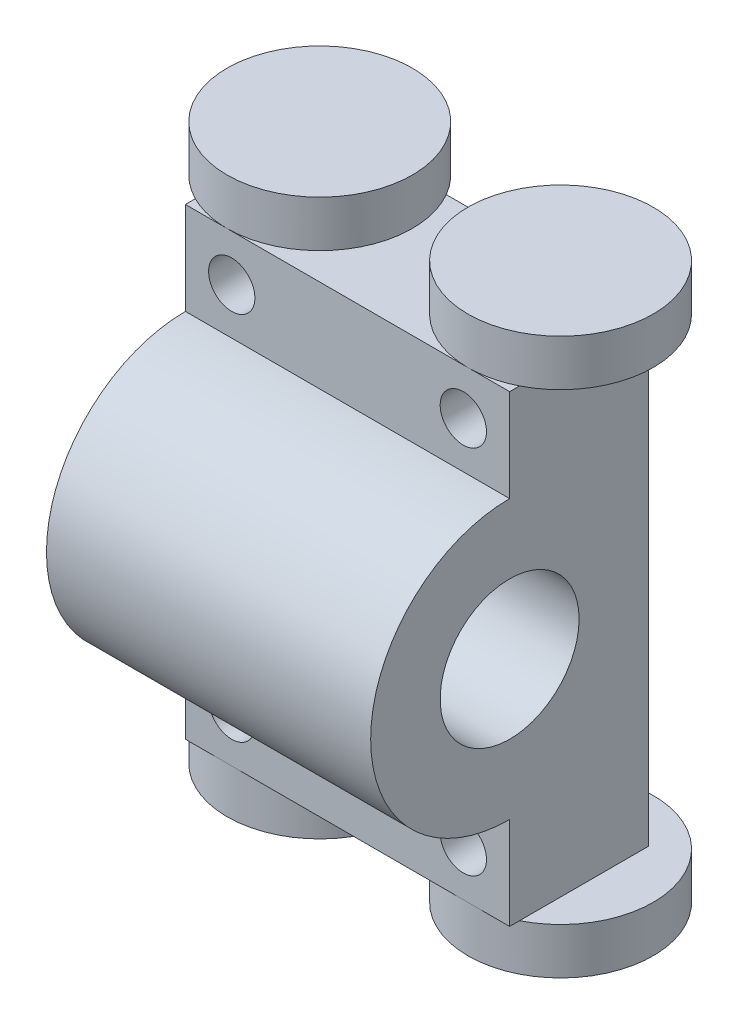
SolidWorks part; units mm, degrees
ref_plane "Front Plane" through (0, 0, 0) normal (0, 0, 1) x (1, 0, 0)
ref_plane "Top Plane" through (0, 0, 0) normal (0, 1, 0) x (1, 0, 0)
ref_plane "Right Plane" through (0, 0, 0) normal (1, 0, 0) x (0, 0, -1)
sketch "Sketch1" plane through (0, 0, 0) normal (1, 0, 0) x (0, 0, -1)
  line L5 (0, 0) -> (-30, 0) construction
  line L6 (-15, -15) -> (-15, -25)
  line L7 (-15, 25) -> (0, 25)
  line L8 (-15, 25) -> (-15, 15)
  line L9 (-15, -25) -> (0, -25)
  line L10 (0, 25) -> (0, -25)
  arc A0 (-15, 15) -> (-15, -15) centre (-15, 0) ccw
  point P0 (0, 0)
  dimension "D1" = 15
  dimension "D2" = 50
  dimension "D3" = 15
extrude "body" add sketch "Sketch1" along normal blind 35
sketch "Sketch3" plane through (35, 0, 0) normal (1, 0, 0) x (0, 0, -1)
  circle A0 centre (-15, 0) radius 7.5
  arc A1 (-15, 15) -> (-15, -15) centre (-15, 0) ccw construction
  dimension "D1" = 15
extrude "shaft hole" cut sketch "Sketch3" against normal blind 40
sketch "Sketch4" plane through (0, 25, 0) normal (0, 1, 0) x (1, 0, 0)
  line L0 (17.5, -15) -> (17.5, -6.3939) construction
  line L3 (35, 0) -> (0, 0) construction
  circle A0 centre (4.5, -5) radius 2.5
  circle A1 centre (30.5, -5) radius 2.5
  point P9 (17.5, 0)
  dimension "D1" = 5
  dimension "D2" = 26
  dimension "D3" = 5
extrude "Boss-Extrude1" add sketch "Sketch4" along normal blind 5
mirror "Mirror1" about plane through (0, 0, 0) normal (0, 1, 0) of "Boss-Extrude1"
sketch "Sketch5" plane through (0, 30, 0) normal (0, 1, 0) x (1, 0, 0)
  circle A0 centre (4.5, -5) radius 10
  dimension "D1" = 20
extrude "bearing" add sketch "Sketch5" against normal blind 5
mirror "Mirror2" about plane through (0, 0, 0) normal (0, 1, 0) of "bearing"
ref_plane "Plane1" through (17.5, 0, 0) normal (1, 0, 0) x (0, 0, -1)
mirror "Mirror5" about plane through (17.5, 0, 0) normal (1, 0, 0) of "bearing", "Mirror2"
sketch "Sketch6" plane through (0, 0, 15) normal (0, 0, 1) x (1, 0, 0)
  line L0 (30.5, 25) -> (4.5, 25) construction
  line L2 (0, 25) -> (0, 15) construction
  line L3 (17.5, 25) -> (17.5, -25) construction
  line L4 (30.5, -25) -> (4.5, -25) construction
  line L5 (0, 0) -> (35, 0) construction
  line L6 (35, -15) -> (35, 15) construction
  circle A0 centre (5, 20) radius 2.5
  circle A4 centre (30, 20) radius 2.5
  circle A5 centre (30, -20) radius 2.5
  circle A6 centre (5, -20) radius 2.5
  dimension "D1" = 5
  dimension "D2" = 5
  dimension "D3" = 5
extrude "Cut-Extrude1" cut sketch "Sketch6" against normal through all
